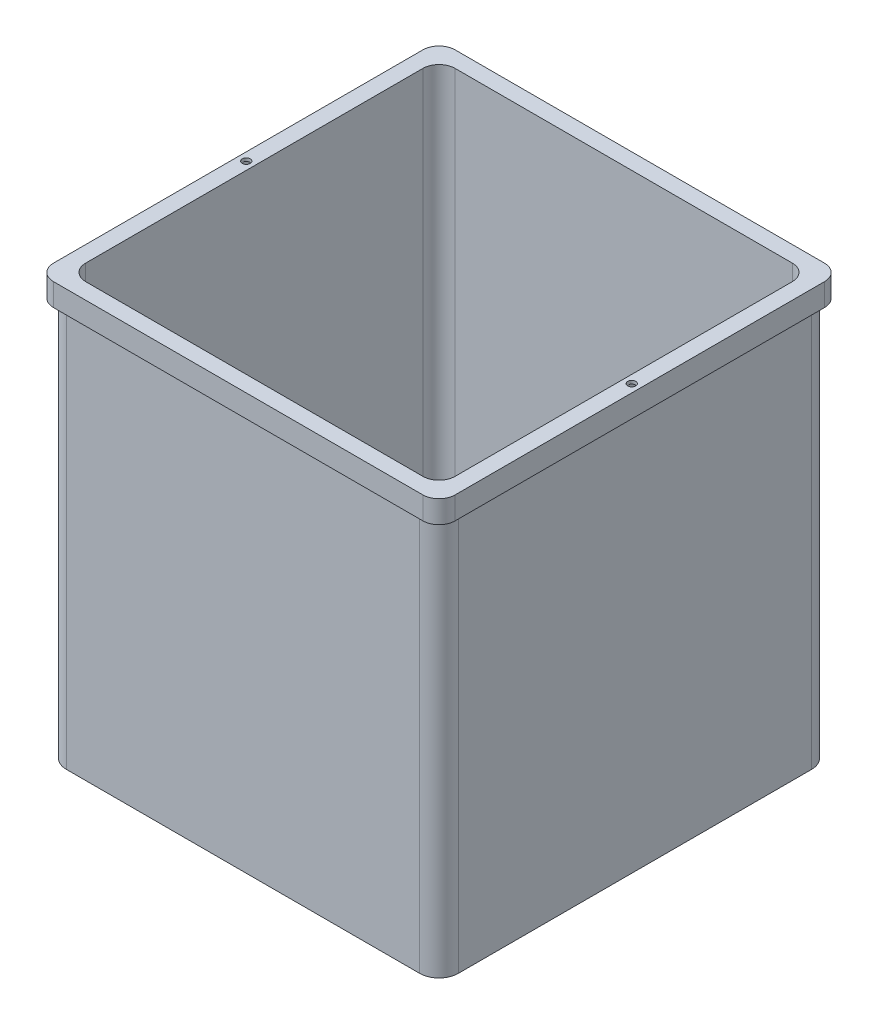
SolidWorks part; units mm, degrees
ref_plane "前视基准面" through (0, 0, 0) normal (0, 0, 1) x (1, 0, 0)
ref_plane "上视基准面" through (0, 0, 0) normal (0, 1, 0) x (1, 0, 0)
ref_plane "右视基准面" through (0, 0, 0) normal (1, 0, 0) x (0, 0, -1)
other "Configuration Table"
sketch "草图1" plane through (0, 0, 0) normal (0, 1, 0) x (1, 0, 0)
  line L1 (-55, 60) -> (55, 60)
  line L2 (-60, 55) -> (-60, -55)
  line L3 (-55, -60) -> (55, -60)
  line L4 (60, 55) -> (60, -55)
  line L5 (-60, 60) -> (60, -60) construction
  line L6 (-60, -60) -> (60, 60) construction
  arc A0 (-60, 55) -> (-55, 60) centre (-55, 55) cw
  arc A1 (60, 55) -> (55, 60) centre (55, 55) ccw
  arc A2 (-55, -60) -> (-60, -55) centre (-55, -55) cw
  arc A3 (60, -55) -> (55, -60) centre (55, -55) cw
  point P0 (0, 0)
  dimension "D3" = 5
  dimension "D4" = 5
  dimension "D5" = 5
  dimension "D6" = 5
  dimension "D1" = 120
  dimension "D2" = 120
extrude "拉伸-薄壁1" add sketch "草图1" along normal blind 125 thin thin type one direction wall 1
ref_plane "基准面1" through (0, 5, 0) normal (0, 1, 0) x (1, 0, 0)
sketch "草图2" plane through (0, 5, 0) normal (0, 1, 0) x (1, 0, 0)
  line L0 (-60, 55) -> (-60, -55) construction
  line L1 (-55, -60) -> (55, -60) construction
  line L2 (60, -55) -> (60, 55) construction
  line L3 (55, 60) -> (-55, 60) construction
  line L4 (-60, 55) -> (-60, -55)
  line L5 (-55, -60) -> (55, -60)
  line L6 (60, -55) -> (60, 55)
  line L7 (55, 60) -> (-55, 60)
  arc A0 (-60, -55) -> (-55, -60) centre (-55, -55) ccw construction
  arc A1 (55, -60) -> (60, -55) centre (55, -55) ccw construction
  arc A2 (60, 55) -> (55, 60) centre (55, 55) ccw construction
  arc A3 (-55, 60) -> (-60, 55) centre (-55, 55) ccw construction
  arc A4 (-60, -55) -> (-55, -60) centre (-55, -55) ccw
  arc A5 (55, -60) -> (60, -55) centre (55, -55) ccw
  arc A6 (60, 55) -> (55, 60) centre (55, 55) ccw
  arc A7 (-55, 60) -> (-60, 55) centre (-55, 55) ccw
extrude "凸台-拉伸1" add sketch "草图2" along normal blind 1
ref_plane "基准面2" through (0, 15, 0) normal (0, 1, 0) x (1, 0, 0)
sketch "草图4" plane through (0, 15, 0) normal (0, 1, 0) x (1, 0, 0)
  line L1 (-52.5, 57.5) -> (52.5, 57.5)
  line L2 (-57.5, 52.5) -> (-57.5, -52.5)
  line L3 (-52.5, -57.5) -> (52.5, -57.5)
  line L4 (57.5, 52.5) -> (57.5, -52.5)
  line L5 (-57.5, 57.5) -> (57.5, -57.5) construction
  line L6 (-57.5, -57.5) -> (57.5, 57.5) construction
  arc A0 (52.5, 57.5) -> (57.5, 52.5) centre (52.5, 52.5) cw
  arc A1 (57.5, -52.5) -> (52.5, -57.5) centre (52.5, -52.5) cw
  arc A2 (-52.5, -57.5) -> (-57.5, -52.5) centre (-52.5, -52.5) cw
  arc A3 (-57.5, 52.5) -> (-52.5, 57.5) centre (-52.5, 52.5) cw
  point P0 (0, 0)
  dimension "D3" = 5
  dimension "D1" = 115
  dimension "D2" = 115
extrude "拉伸-薄壁2" add sketch "草图4" along normal blind 115 separate body thin thin type one direction wall 1
ref_plane "基准面3" through (0, 130, 0) normal (0, 1, 0) x (1, 0, 0)
sketch "草图5" plane through (0, 130, 0) normal (0, 1, 0) x (1, 0, 0)
  line L0 (-57.5, 52.5) -> (-57.5, -52.5) construction
  line L1 (-57.5, 62.5) -> (57.5, 62.5)
  line L2 (-62.5, 57.5) -> (-62.5, -57.5)
  line L3 (-57.5, -62.5) -> (57.5, -62.5)
  line L4 (62.5, 57.5) -> (62.5, -57.5)
  line L5 (-62.5, 62.5) -> (62.5, -62.5) construction
  line L6 (-62.5, -62.5) -> (62.5, 62.5) construction
  line L7 (-52.5, -57.5) -> (52.5, -57.5) construction
  line L8 (57.5, -52.5) -> (57.5, 52.5) construction
  line L9 (52.5, 57.5) -> (-52.5, 57.5) construction
  line L10 (-57.5, 52.5) -> (-57.5, -52.5)
  line L11 (-52.5, -57.5) -> (52.5, -57.5)
  line L12 (57.5, -52.5) -> (57.5, 52.5)
  line L13 (52.5, 57.5) -> (-52.5, 57.5)
  line L14 (-60, 55) -> (-60, -55) construction
  line L15 (60, -55) -> (60, 55) construction
  arc A0 (57.5, 62.5) -> (62.5, 57.5) centre (57.5, 57.5) cw
  arc A1 (62.5, -57.5) -> (57.5, -62.5) centre (57.5, -57.5) cw
  arc A2 (-57.5, -62.5) -> (-62.5, -57.5) centre (-57.5, -57.5) cw
  arc A3 (-62.5, 57.5) -> (-57.5, 62.5) centre (-57.5, 57.5) cw
  arc A4 (-52.5, 57.5) -> (-57.5, 52.5) centre (-52.5, 52.5) ccw construction
  arc A5 (-57.5, -52.5) -> (-52.5, -57.5) centre (-52.5, -52.5) ccw construction
  arc A6 (52.5, -57.5) -> (57.5, -52.5) centre (52.5, -52.5) ccw construction
  arc A7 (57.5, 52.5) -> (52.5, 57.5) centre (52.5, 52.5) ccw construction
  arc A8 (-52.5, 57.5) -> (-57.5, 52.5) centre (-52.5, 52.5) ccw
  arc A9 (-57.5, -52.5) -> (-52.5, -57.5) centre (-52.5, -52.5) ccw
  arc A10 (52.5, -57.5) -> (57.5, -52.5) centre (52.5, -52.5) ccw
  arc A11 (57.5, 52.5) -> (52.5, 57.5) centre (52.5, 52.5) ccw
  circle A12 centre (-60, 0) radius 1.25
  circle A13 centre (60, 0) radius 1.25
  point P0 (0, 0)
  dimension "D3" = 5
  dimension "D1" = 125
  dimension "D2" = 125
extrude "凸台-拉伸3" add sketch "草图5" along normal blind 1
ref_plane "基准面4" through (0, 125, 0) normal (0, 1, 0) x (1, 0, 0)
sketch "草图7" plane through (0, 125, 0) normal (0, 1, 0) x (1, 0, 0)
  line L0 (62.5, -57.5) -> (62.5, 57.5) construction
  line L1 (-57.5, -62.5) -> (57.5, -62.5) construction
  line L2 (-62.5, 57.5) -> (-62.5, -57.5) construction
  line L3 (57.5, 62.5) -> (-57.5, 62.5) construction
  line L4 (62.5, -57.5) -> (62.5, 57.5)
  line L5 (-57.5, -62.5) -> (57.5, -62.5)
  line L6 (-62.5, 57.5) -> (-62.5, -57.5)
  line L7 (57.5, 62.5) -> (-57.5, 62.5)
  line L9 (-56.5, -61.5) -> (56.5, -61.5)
  line L10 (-61.5, -56.5) -> (-61.5, 56.5)
  line L11 (-56.5, 61.5) -> (56.5, 61.5)
  line L12 (61.5, -56.5) -> (61.5, 56.5)
  line L13 (-61.5, -61.5) -> (61.5, 61.5) construction
  line L14 (-61.5, 61.5) -> (61.5, -61.5) construction
  arc A0 (62.5, 57.5) -> (57.5, 62.5) centre (57.5, 57.5) ccw construction
  arc A1 (57.5, -62.5) -> (62.5, -57.5) centre (57.5, -57.5) ccw construction
  arc A2 (-62.5, -57.5) -> (-57.5, -62.5) centre (-57.5, -57.5) ccw construction
  arc A3 (-57.5, 62.5) -> (-62.5, 57.5) centre (-57.5, 57.5) ccw construction
  arc A4 (62.5, 57.5) -> (57.5, 62.5) centre (57.5, 57.5) ccw
  arc A5 (57.5, -62.5) -> (62.5, -57.5) centre (57.5, -57.5) ccw
  arc A6 (-62.5, -57.5) -> (-57.5, -62.5) centre (-57.5, -57.5) ccw
  arc A7 (-57.5, 62.5) -> (-62.5, 57.5) centre (-57.5, 57.5) ccw
  arc A8 (61.5, -56.5) -> (56.5, -61.5) centre (56.5, -56.5) cw
  arc A9 (-56.5, -61.5) -> (-61.5, -56.5) centre (-56.5, -56.5) cw
  arc A10 (-61.5, 56.5) -> (-56.5, 61.5) centre (-56.5, 56.5) cw
  arc A11 (61.5, 56.5) -> (56.5, 61.5) centre (56.5, 56.5) ccw
  point P4 (0, 0)
  dimension "D3" = 5
  dimension "D1" = 1
  dimension "D2" = 1
extrude "凸台-拉伸4" add sketch "草图7" along normal up to next
ref_plane "基准面5" through (0, 125, 0) normal (0, 1, 0) x (1, 0, 0)
sketch "草图8" plane through (0, 125, 0) normal (0, 1, 0) x (1, 0, 0)
  line L0 (-62.5, 57.5) -> (-62.5, -57.5) construction
  line L1 (-57.5, -62.5) -> (57.5, -62.5) construction
  line L2 (62.5, -57.5) -> (62.5, 57.5) construction
  line L3 (57.5, 62.5) -> (-57.5, 62.5) construction
  line L4 (-62.5, 57.5) -> (-62.5, -57.5)
  line L5 (-57.5, -62.5) -> (57.5, -62.5)
  line L6 (62.5, -57.5) -> (62.5, 57.5)
  line L7 (57.5, 62.5) -> (-57.5, 62.5)
  line L8 (55, 61) -> (-55, 61) construction
  line L9 (-61, 55) -> (-61, -55) construction
  line L10 (-55, -61) -> (55, -61) construction
  line L11 (61, -55) -> (61, 55) construction
  line L12 (55, 61) -> (-55, 61)
  line L13 (-61, 55) -> (-61, -55)
  line L14 (-55, -61) -> (55, -61)
  line L15 (61, -55) -> (61, 55)
  arc A0 (-57.5, 62.5) -> (-62.5, 57.5) centre (-57.5, 57.5) ccw construction
  arc A1 (-62.5, -57.5) -> (-57.5, -62.5) centre (-57.5, -57.5) ccw construction
  arc A2 (57.5, -62.5) -> (62.5, -57.5) centre (57.5, -57.5) ccw construction
  arc A3 (62.5, 57.5) -> (57.5, 62.5) centre (57.5, 57.5) ccw construction
  arc A4 (-57.5, 62.5) -> (-62.5, 57.5) centre (-57.5, 57.5) ccw
  arc A5 (-62.5, -57.5) -> (-57.5, -62.5) centre (-57.5, -57.5) ccw
  arc A6 (57.5, -62.5) -> (62.5, -57.5) centre (57.5, -57.5) ccw
  arc A7 (62.5, 57.5) -> (57.5, 62.5) centre (57.5, 57.5) ccw
  arc A8 (-55, 61) -> (-61, 55) centre (-55, 55) ccw construction
  arc A9 (-61, -55) -> (-55, -61) centre (-55, -55) ccw construction
  arc A10 (55, -61) -> (61, -55) centre (55, -55) ccw construction
  arc A11 (61, 55) -> (55, 61) centre (55, 55) ccw construction
  arc A12 (-55, 61) -> (-61, 55) centre (-55, 55) ccw
  arc A13 (-61, -55) -> (-55, -61) centre (-55, -55) ccw
  arc A14 (55, -61) -> (61, -55) centre (55, -55) ccw
  arc A15 (61, 55) -> (55, 61) centre (55, 55) ccw
extrude "凸台-拉伸5" add sketch "草图8" against normal blind 1
